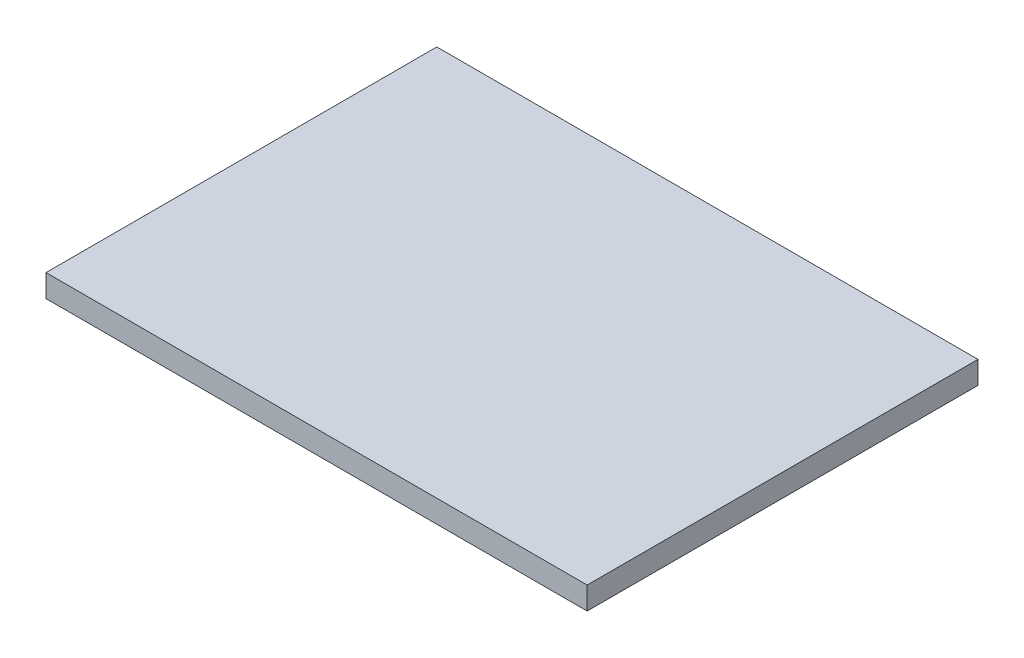
SolidWorks part; units mm, degrees
ref_plane "Front Plane" through (0, 0, 0) normal (0, 0, 1) x (1, 0, 0)
ref_plane "Top Plane" through (0, 0, 0) normal (0, 1, 0) x (1, 0, 0)
ref_plane "Right Plane" through (0, 0, 0) normal (1, 0, 0) x (0, 0, -1)
sketch "Sketch1" plane through (0, 0, 0) normal (0, 1, 0) x (1, 0, 0)
  line L1 (-36, -26) -> (36, -26)
  line L2 (-36, -26) -> (-36, 26)
  line L3 (-36, 26) -> (36, 26)
  line L4 (36, -26) -> (36, 26)
  line L5 (-36, -26) -> (36, 26) construction
  line L6 (-36, 26) -> (36, -26) construction
  point P0 (0, 0)
  dimension "D1" = 72
  dimension "D2" = 52
extrude "Boss-Extrude1" add sketch "Sketch1" along normal blind 3
